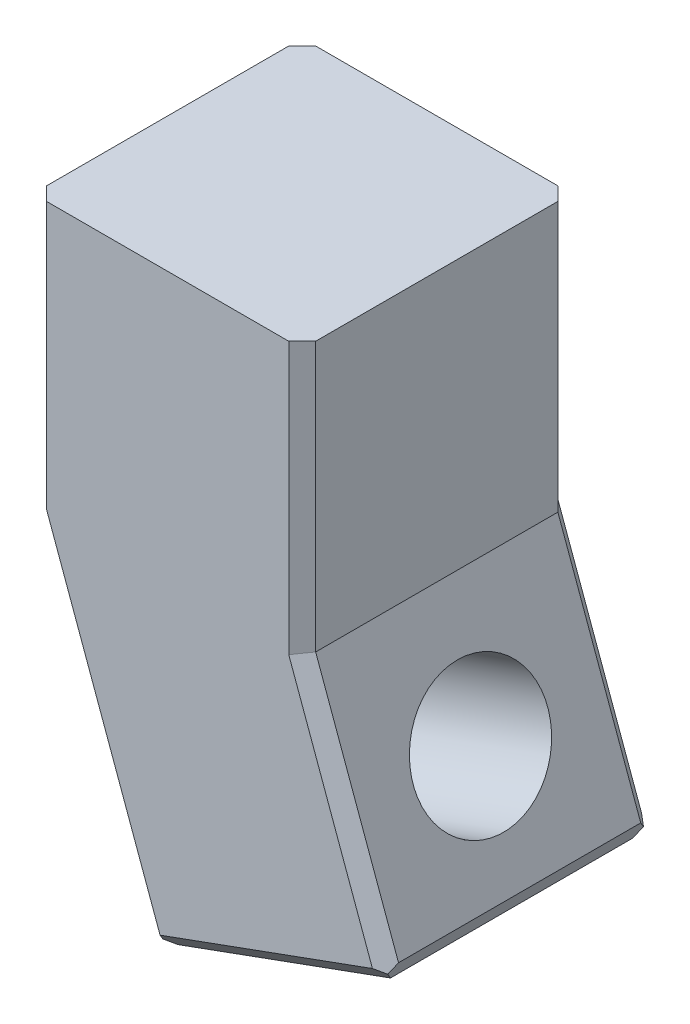
SolidWorks part; units mm, degrees
ref_plane "前视基准面" through (0, 0, 0) normal (0, 0, 1) x (1, 0, 0)
ref_plane "上视基准面" through (0, 0, 0) normal (0, 1, 0) x (1, 0, 0)
ref_plane "右视基准面" through (0, 0, 0) normal (1, 0, 0) x (0, 0, -1)
other "Configuration Table"
sketch "草图1" plane through (0, 0, 0) normal (0, 0, 1) x (1, 0, 0)
  line L0 (10, -10) -> (16.5005, -27.8601)
  line L2 (-10, -10) -> (-10, 10)
  line L3 (-10, 10) -> (10, 10)
  line L4 (10, -10) -> (10, 10)
  line L5 (-10, -10) -> (10, 10) construction
  line L6 (-10, 10) -> (10, -10) construction
  line L7 (-10, -10) -> (-1.1599, -34.2879)
  line L8 (16.5005, -27.8601) -> (-1.1599, -34.2879)
  point P0 (0, 0)
  point P6 (10.0302, -9.9099)
  dimension "D1" = 20
  dimension "D2" = 20
  dimension "D3" = 160
extrude "凸台-拉伸1" add sketch "草图1" along normal blind 20
sketch "草图2" plane through (5.6163, 2.0442, 0) normal (0.9397, 0.342, 0) x (0, 0, -1)
  line L0 (-10, -12.8171) -> (-10, -31.8234) construction
  line L1 (-20, -12.8171) -> (0, -12.8171) construction
  line L2 (-20, -31.8234) -> (0, -31.8234) construction
  circle A0 centre (-10, -22.3203) radius 5
  dimension "D1" = 10
extrude "切除-拉伸1" cut sketch "草图2" against normal blind 20
chamfer "倒角1" distance 1 angle 45 4 edges at (-1.1599, -34.2879, 10) (7.6703, -31.074, 20) (16.5005, -27.8601, 10) (7.6703, -31.074, 0)
chamfer "倒角2" distance 1 angle 45 8 edges at (-5.751, -21.6741, 0) (-10, 0, 0) (13.0793, -18.4602, 0) (10, 0, 0) (13.0793, -18.4602, 20) (10, 0, 20) (-5.751, -21.6741, 20) (-10, 0, 20)
